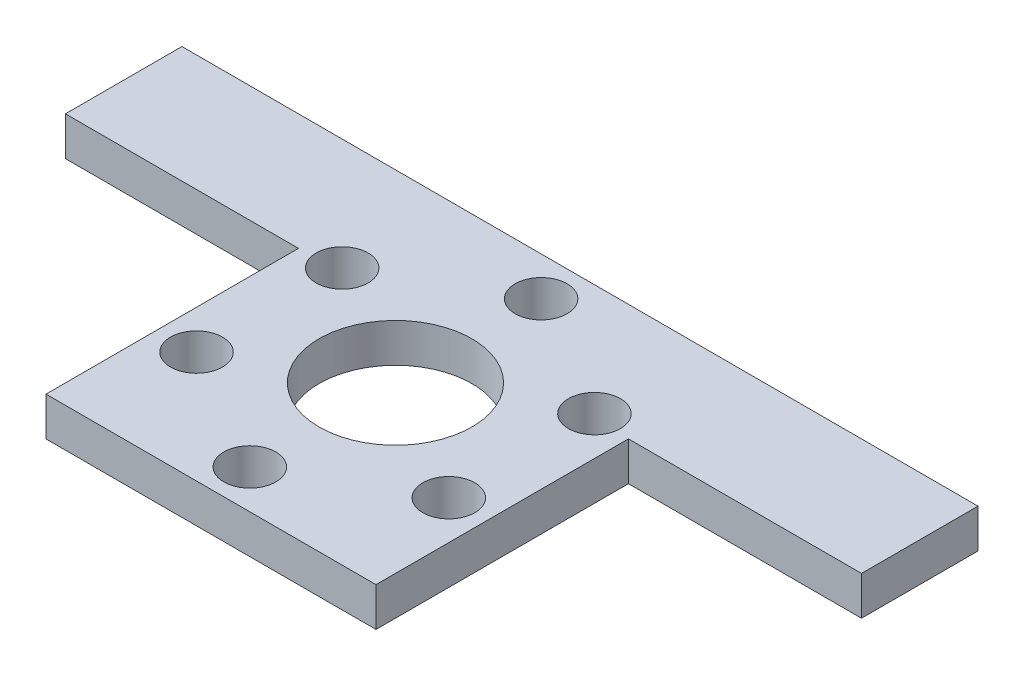
SolidWorks part; units mm, degrees
ref_plane "Front Plane" through (0, 0, 0) normal (0, 0, 1) x (1, 0, 0)
ref_plane "Top Plane" through (0, 0, 0) normal (0, 1, 0) x (1, 0, 0)
ref_plane "Right Plane" through (0, 0, 0) normal (1, 0, 0) x (0, 0, -1)
sketch "Sketch1" plane through (0, 0, 0) normal (0, 1, 0) x (1, 0, 0)
  line L0 (10.7889, 4.445) -> (26.0289, 4.445)
  line L1 (0, 9.525) -> (-8.2489, 4.7625) construction
  line L2 (-8.2489, 4.7625) -> (-8.2489, -4.7625) construction
  line L3 (-8.2489, -4.7625) -> (0, -9.525) construction
  line L4 (0, -9.525) -> (8.2489, -4.7625) construction
  line L5 (8.2489, -4.7625) -> (8.2489, 4.7625) construction
  line L6 (8.2489, 4.7625) -> (0, 9.525) construction
  line L8 (-10.7889, 4.445) -> (-10.7889, -12.065)
  line L9 (-10.7889, -12.065) -> (10.7889, -12.065)
  line L10 (10.7889, 4.445) -> (10.7889, -12.065)
  line L11 (-26.0289, 12.065) -> (26.0289, 12.065)
  line L12 (-26.0289, 12.065) -> (-26.0289, 4.445)
  line L13 (-26.0289, 4.445) -> (-10.7889, 4.445)
  line L14 (26.0289, 12.065) -> (26.0289, 4.445)
  circle A0 centre (0, 0) radius 5
  circle A1 centre (0, 0) radius 8.2489 construction
  point P18 (0, 0)
  point P19 (0, 0)
  point P20 (0, 0)
  point P21 (0, 0)
  point P22 (0, 0)
  point P23 (-10.7889, -12.065)
  point P24 (0, 0)
  dimension "D1" = 10
  dimension "D2" = 9.525
  dimension "D3" = 2.54
  dimension "D4" = 2.54
  dimension "D5" = 2.54
  dimension "D6" = 2.54
  dimension "D7" = 7.62
  dimension "D8" = 15.24
  dimension "D9" = 15.24
extrude "Boss-Extrude1" add sketch "Sketch1" along normal blind 2.54
sketch "Sketch2" plane through (0, 2.54, 0) normal (0, 1, 0) x (1, 0, 0)
  line L1 (0, 9.525) -> (-8.2489, 4.7625) construction
  line L2 (-8.2489, 4.7625) -> (-8.2489, -4.7625) construction
  line L3 (-8.2489, -4.7625) -> (0, -9.525) construction
  line L4 (0, -9.525) -> (8.2489, -4.7625) construction
  line L5 (8.2489, -4.7625) -> (8.2489, 4.7625) construction
  line L6 (8.2489, 4.7625) -> (0, 9.525) construction
  circle A0 centre (0, 0) radius 8.2489 construction
  dimension "D1" = 9.525
hole_wizard "M3 Clearance Hole1" positions "Sketch3" profile "Sketch4" hole size "M3" standard "ANSI Metric" end condition through all
sketch "Sketch3" plane through (0, 2.54, 0) normal (0, 1, 0) x (1, 0, 0)
  point P0 (0, 9.525)
  point P3 (8.2489, 4.7625)
  point P6 (8.2489, -4.7625)
  point P9 (0, -9.525)
  point P12 (-8.2489, -4.7625)
  point P15 (-8.2489, 4.7625)
sketch "Sketch4" plane through (0, 2.54, -9.525) normal (1, 0, 0) x (0, 0, 1)
  line L0 (0, 0) -> (0, 2.54)
  line L1 (0, 2.54) -> (1.7, 2.54)
  line L2 (1.7, 2.54) -> (1.7, 0)
  line L5 (1.7, 0) -> (0, 0)
  line L11 (0, -6.35) -> (0, 107.95) construction
  dimension "Thru Hole Dia." = 3.4
  dimension "Thru Hole Depth" = 2.54
